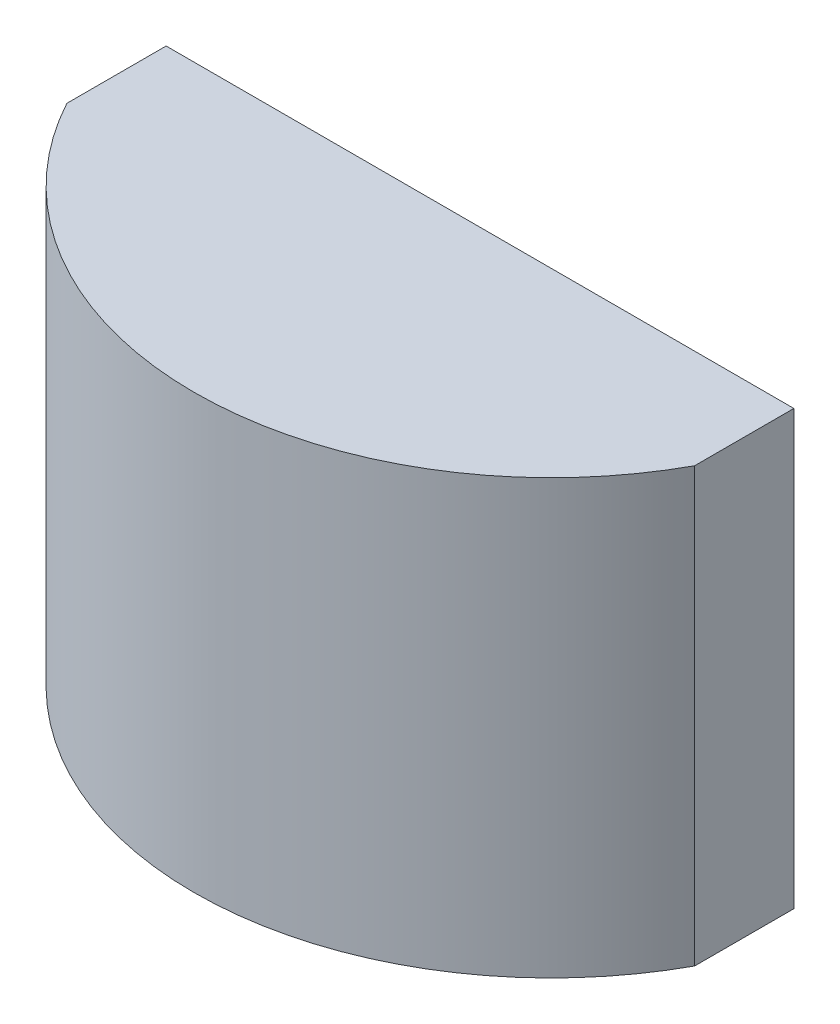
SolidWorks part; units mm, degrees
ref_plane "Front Plane" through (0, 0, 0) normal (0, 0, 1) x (1, 0, 0)
ref_plane "Top Plane" through (0, 0, 0) normal (0, 1, 0) x (1, 0, 0)
ref_plane "Right Plane" through (0, 0, 0) normal (1, 0, 0) x (0, 0, -1)
sketch "Sketch1" plane through (0, 0, 0) normal (0, 1, 0) x (1, 0, 0)
  line L0 (65.2, -14.8) -> (-65.2, -14.8)
  line L1 (-65.2, -14.8) -> (-65.2, -35.4203)
  line L2 (65.2, -35.4203) -> (65.2, -14.8)
  arc A0 (-65.2, -35.4203) -> (65.2, -35.4203) centre (0, 0) ccw
  point P5 (0, 0)
  point P7 (-63.5305, -20.8317)
  dimension "D3" = 74.2
  dimension "D1" = 130.4
  dimension "D2" = 20.6203
extrude "Boss-Extrude1" add sketch "Sketch1" along normal blind 90
